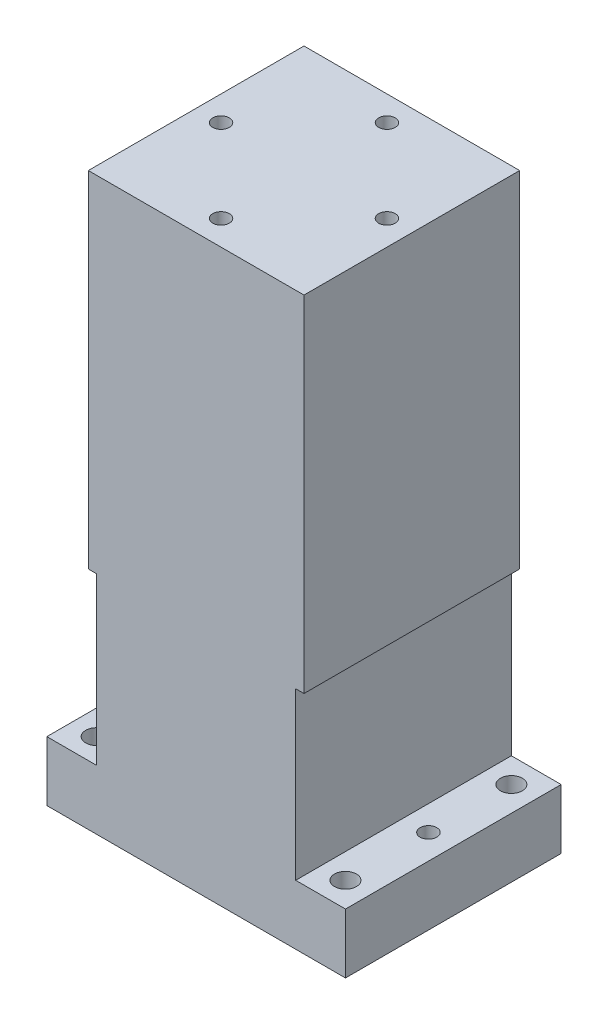
SolidWorks part; units mm, degrees
ref_plane "Ebene vorne" through (0, 0, 0) normal (0, 0, 1) x (1, 0, 0)
ref_plane "Ebene oben" through (0, 0, 0) normal (0, 1, 0) x (1, 0, 0)
ref_plane "Ebene rechts" through (0, 0, 0) normal (1, 0, 0) x (0, 0, -1)
ref_plane "Ebene4" through (0, 0, -32.5) normal (0, 0, -1) x (-1, 0, 0)
sketch "Skizze1" plane through (0, 0, -32.5) normal (0, 0, -1) x (-1, 0, 0)
  line L0 (45, 0) -> (45, 172)
  line L1 (45, 172) -> (-45, 172)
  line L2 (-45, 172) -> (-45, 0)
  line L3 (-45, 0) -> (45, 0)
extrude "Aufsatz-Linear austragen1" add sketch "Skizze1" against normal blind 65
sketch "Skizze2" plane through (0, 0, 32.5) normal (0, 0, 1) x (1, 0, 0)
  line L0 (-45, 18) -> (-30, 18)
  line L1 (-30, 18) -> (-30, 172)
  line L2 (-30, 172) -> (-45, 172)
  line L3 (-45, 172) -> (-45, 18)
extrude "Schnitt-Linear austragen1" cut sketch "Skizze2" against normal through all
sketch "Skizze3" plane through (-30, 0, 0) normal (-1, 0, 0) x (0, 0, 1)
  line L0 (-32.5, 172) -> (32.5, 172)
  line L1 (32.5, 172) -> (32.5, 68)
  line L2 (32.5, 68) -> (-32.5, 68)
  line L3 (-32.5, 68) -> (-32.5, 172)
extrude "Aufsatz-Linear austragen2" add sketch "Skizze3" along normal blind 2.5
sketch "Skizze4" plane through (0, 0, 32.5) normal (0, 0, 1) x (1, 0, 0)
  line L0 (30, 172) -> (30, 18)
  line L1 (30, 18) -> (45, 18)
  line L2 (45, 18) -> (45, 172)
  line L3 (45, 172) -> (30, 172)
extrude "Schnitt-Linear austragen2" cut sketch "Skizze4" against normal through all
sketch "Skizze5" plane through (30, 0, 0) normal (1, 0, 0) x (0, 0, -1)
  line L0 (32.5, 68) -> (-32.5, 68)
  line L1 (-32.5, 68) -> (-32.5, 172)
  line L2 (-32.5, 172) -> (32.5, 172)
  line L3 (32.5, 172) -> (32.5, 68)
extrude "Aufsatz-Linear austragen3" add sketch "Skizze5" along normal blind 2.5
hole_wizard "Ø6.6 (6.6) Durchmesser Bohrung1" positions "Skizze7" profile "Skizze6" hole size "Ø6.6" standard "ANSI Metrisch"
sketch "Skizze7" plane through (0, 0, 0) normal (0, -1, 0) x (-1, 0, 0)
  point P0 (37.5, -25)
  point P1 (37.5, 25)
sketch "Skizze6" plane through (-37.5, 0, 25) normal (1, 0, 0) x (0, 0, -1)
  line L0 (0, 0) -> (0, 172)
  line L1 (0, 172) -> (3.3, 172)
  line L2 (3.3, 172) -> (3.3, 0)
  line L5 (3.3, 0) -> (0, 0)
  line L11 (0, -6.35) -> (0, 107.95) construction
  dimension "Bohrerdurchmesser" = 6.6
  dimension "Bohrungstiefe" = 172
hole_wizard "Bohrung1" positions "Skizze9" profile "Skizze8" legacy
sketch "Skizze9" plane through (0, 0, 0) normal (0, -1, 0) x (-1, 0, 0)
  point P0 (37.5, 0)
sketch "Skizze8" plane through (-37.5, 0, 0) normal (1, 0, 0) x (0, 0, -1)
  line L0 (0, 0) -> (0, 172)
  line L1 (0, 172) -> (2.51, 172)
  line L2 (2.51, 172) -> (2.51, 0)
  line L3 (2.51, 0) -> (0, 0)
  line L4 (0, 110) -> (0, -10) construction
  dimension "Durchmesser" = 5.02
  dimension "Tiefe" = 172
hole_wizard "Ø6.6 (6.6) Durchmesser Bohrung2" positions "Skizze11" profile "Skizze10" hole size "Ø6.6" standard "ANSI Metrisch"
sketch "Skizze11" plane through (0, 18, 0) normal (0, 1, 0) x (1, 0, 0)
  point P0 (37.5, 25)
  point P1 (37.5, -25)
sketch "Skizze10" plane through (37.5, 18, -25) normal (1, 0, 0) x (0, 0, 1)
  line L0 (0, 0) -> (0, 18)
  line L1 (0, 18) -> (3.3, 18)
  line L2 (3.3, 18) -> (3.3, 0)
  line L5 (3.3, 0) -> (0, 0)
  line L11 (0, -6.35) -> (0, 107.95) construction
  dimension "Bohrerdurchmesser" = 6.6
  dimension "Bohrungstiefe" = 18
hole_wizard "Bohrung2" positions "Skizze13" profile "Skizze12" legacy
sketch "Skizze13" plane through (0, 18, 0) normal (0, 1, 0) x (1, 0, 0)
  point P0 (37.5, 0)
sketch "Skizze12" plane through (37.5, 18, 0) normal (1, 0, 0) x (0, 0, 1)
  line L0 (0, 0) -> (0, 18)
  line L1 (0, 18) -> (2.51, 18)
  line L2 (2.51, 18) -> (2.51, 0)
  line L3 (2.51, 0) -> (0, 0)
  line L4 (0, 110) -> (0, -10) construction
  dimension "Durchmesser" = 5.02
  dimension "Tiefe" = 18
hole_wizard "Ø5.0 (5) Durchmesser Bohrung1" positions "Skizze15" profile "Skizze14" hole size "Ø5.0" standard "ANSI Metrisch"
sketch "Skizze15" plane through (0, 172, 0) normal (0, 1, 0) x (1, 0, 0)
  point P0 (-25, 0)
  point P1 (25, 0)
  point P2 (0, 25)
  point P3 (0, -25)
sketch "Skizze14" plane through (-25, 172, 0) normal (1, 0, 0) x (0, 0, 1)
  line L0 (0, 0) -> (0, 18.5022)
  line L1 (0, 18.5022) -> (2.5, 17)
  line L2 (2.5, 17) -> (2.5, 0)
  line L5 (2.5, 0) -> (0, 0)
  line L10 (0, 18.5022) -> (-2.5, 17) construction
  line L11 (0, -6.35) -> (0, 107.95) construction
  dimension "Bohrerdurchmesser" = 5
  dimension "Bohrungstiefe" = 17
  dimension "Spitzenwinkel" = 118
